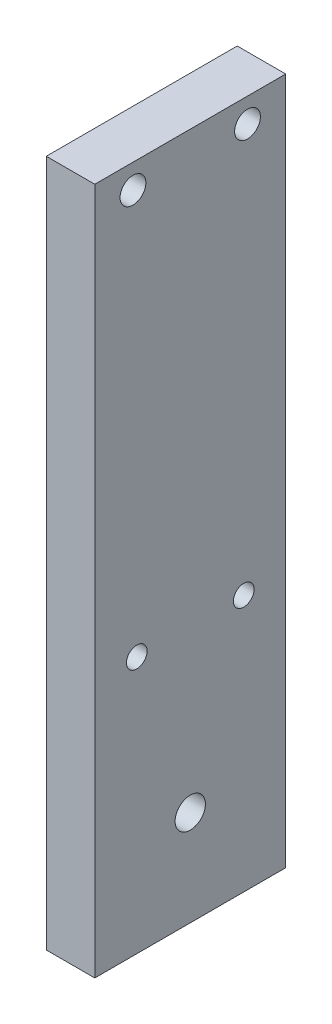
SolidWorks part; units mm, degrees
ref_plane "Alzado" through (0, 0, 0) normal (0, 0, 1) x (1, 0, 0)
ref_plane "Planta" through (0, 0, 0) normal (0, 1, 0) x (1, 0, 0)
ref_plane "Vista lateral" through (0, 0, 0) normal (1, 0, 0) x (0, 0, -1)
sketch "Croquis1" plane through (0, 0, 0) normal (0, 0, 1) x (1, 0, 0)
  line L1 (-6.35, 90) -> (6.35, 90)
  line L2 (-6.35, 90) -> (-6.35, -90)
  line L7 (-6.35, -90) -> (6.35, -90)
  line L8 (6.35, 90) -> (6.35, -90)
  point P4 (0, 90)
  point P6 (-6.35, 0)
  dimension "D2" = 12.7
  dimension "D3" = 180
extrude "Saliente-Extruir1" add sketch "Croquis1" along normal mid plane 50
hole_wizard "Taladro roscado 3/8-161" positions "Croquis3" profile "Croquis4" tap size "3/8-16" standard "Ansi Inch" end condition through all
sketch "Croquis3" plane through (6.35, 0, 0) normal (1, 0, 0) x (0, 0, -1)
  point P0 (0, -65)
sketch "Croquis4" plane through (6.35, -65, 0) normal (0, 1, 0) x (0, 0, -1)
  line L0 (0, 0) -> (0, 12.7)
  line L1 (0, 12.7) -> (3.9687, 12.7)
  line L2 (3.9687, 12.7) -> (3.9687, 0)
  line L5 (3.9687, 0) -> (0, 0)
  line L11 (0, -6.35) -> (0, 107.95) construction
  dimension "Diámetro de perforador para roscar hasta el siguiente" = 7.9375
  dimension "Profundidad de perforador para roscar hasta el siguiente" = 12.7
cosmetic thread "Rosca de taladro4"
hole_wizard "Taladro de margen para 1/41" positions "Croquis5" profile "Croquis6" hole size "1/4" standard "Ansi Inch" end condition through all
sketch "Croquis5" plane through (-6.35, 0, 0) normal (-1, 0, 0) x (0, 0, 1)
  line L0 (0, 0) -> (0, 50000) construction
  point P0 (-15, 83.65)
  point P2 (15, 83.65)
  point P15 (0, 0)
  point P16 (-15, 23.65)
  point P17 (-11.3444, 23.7615)
  point P18 (-14, -2.7)
  point P20 (-14, -2.7)
  point P22 (0, 0)
  dimension "D1" = 6.35
  dimension "D2" = 15
sketch "Croquis6" plane through (-6.35, 83.65, -15) normal (0, 1, 0) x (0, 0, 1)
  line L0 (0, 0) -> (0, 12.7)
  line L1 (0, 12.7) -> (3.3782, 12.7)
  line L2 (3.3782, 12.7) -> (3.3782, 0)
  line L5 (3.3782, 0) -> (0, 0)
  line L11 (0, -6.35) -> (0, 107.95) construction
  dimension "Diámetro de taladro hasta el siguiente" = 6.7564
  dimension "Profundidad de taladro hasta el siguiente" = 12.7
hole_wizard "Taladro roscado 1/4-201" [suppressed] positions "Croquis7" profile "Croquis8" tap size "1/4-20" standard "Ansi Inch"
sketch "Croquis7" plane through (-6.35, 0, 0) normal (-1, 0, 0) x (0, 0, 1)
  arc A0 (-10, -76) -> (-10, -83) centre (-10, -79.5) ccw construction
  point P2 (0, -79.5)
  point P10 (-13.5, -79.5)
sketch "Croquis8" plane through (-6.35, -79.5, 0) normal (0, 1, 0) x (0, 0, 1)
  line L0 (0, 0) -> (0, 12.7)
  line L1 (0, 12.7) -> (2.5527, 12.7)
  line L2 (2.5527, 12.7) -> (2.5527, 0)
  line L5 (2.5527, 0) -> (0, 0)
  line L11 (0, -6.35) -> (0, 107.95) construction
  dimension "Diámetro de perforador para roscar hasta el siguiente" = 5.1054
  dimension "Profundidad de perforador para roscar hasta el siguiente" = 12.7
cosmetic thread "Rosca de taladro5" [suppressed] parameters "D2"=6.35
hole_wizard "Taladro roscado 1/4-281" positions "Croquis9" profile "Croquis10" tap size "1/4-28" standard "Ansi Inch" end condition through all
sketch "Croquis9" plane through (6.35, 0, 0) normal (1, 0, 0) x (0, 0, -1)
  point P0 (14, -22.7)
  point P3 (-14, -22.7)
sketch "Croquis10" plane through (6.35, -22.7, -14) normal (0, 1, 0) x (0, 0, -1)
  line L0 (0, 0) -> (0, 12.7)
  line L1 (0, 12.7) -> (2.7051, 12.7)
  line L2 (2.7051, 12.7) -> (2.7051, 0)
  line L5 (2.7051, 0) -> (0, 0)
  line L11 (0, -6.35) -> (0, 107.95) construction
  dimension "Diámetro de perforador para roscar hasta el siguiente" = 5.4102
  dimension "Profundidad de perforador para roscar hasta el siguiente" = 12.7
cosmetic thread "Rosca de taladro6"
cosmetic thread "Rosca de taladro7"
